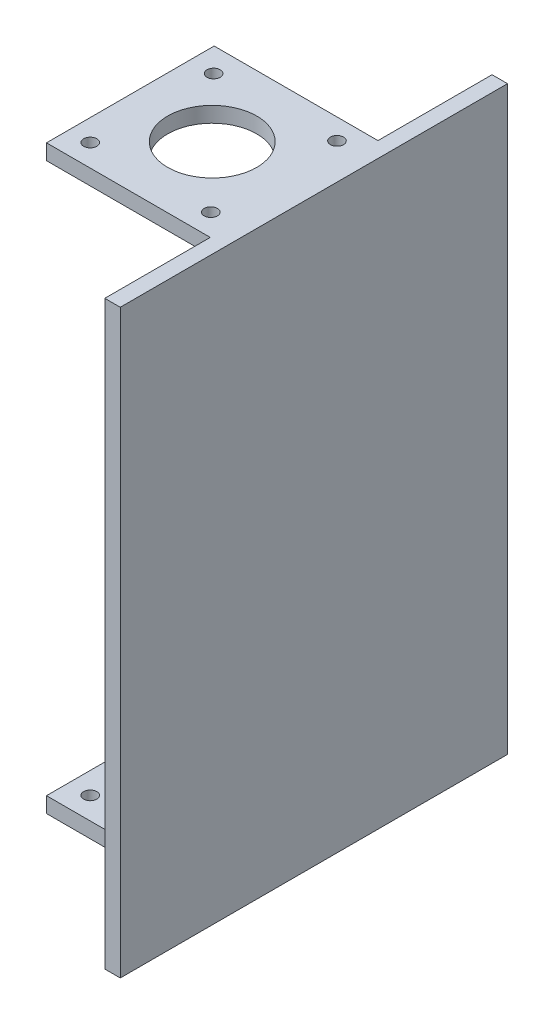
SolidWorks part; units mm, degrees
ref_plane "Front Plane" through (0, 0, 0) normal (0, 0, 1) x (1, 0, 0)
ref_plane "Top Plane" through (0, 0, 0) normal (0, 1, 0) x (1, 0, 0)
ref_plane "Right Plane" through (0, 0, 0) normal (1, 0, 0) x (0, 0, -1)
sketch "Sketch2" plane through (0, 0, 0) normal (0, 1, 0) x (1, 0, 0)
  line L1 (-21.15, -21.65) -> (21.15, -21.65)
  line L2 (-21.15, -21.65) -> (-21.15, 21.65)
  line L3 (-21.15, 21.65) -> (21.15, 21.65)
  line L4 (21.15, -21.65) -> (21.15, 21.65)
  line L5 (-21.15, -21.65) -> (21.15, 21.65) construction
  line L6 (-21.15, 21.65) -> (21.15, -21.65) construction
  circle A0 centre (-15.0694, 15.4256) radius 1.7
  circle A1 centre (15.9184, 16.2948) radius 1.7
  circle A2 centre (15.5664, -15.9344) radius 1.7
  circle A3 centre (-15.5664, -15.9344) radius 1.7
  circle A4 centre (0, 0) radius 11.5
  point P0 (0, 0)
  dimension "D4" = 3.4
  dimension "D5" = 23
  dimension "D1" = 43.3
  dimension "D2" = 42.3
  dimension "D3" = 31
extrude "Boss-Extrude1" add sketch "Sketch2" along normal blind 4
ref_plane "Plane1" through (-21.15, 0, -21.65) normal (-1, 0, 0) x (0, 0, 1)
sketch "Sketch6" plane through (0, 0, -21.65) normal (0, 0, -1) x (-1, 0, 0)
  line L0 (0, 0) -> (28.2537, 0) construction
ref_plane "Plane3" through (-21.15, 4, -21.65) normal (-1, 0, 0) x (0, 0, 1)
ref_plane "Plane4" through (-21.15, 4, -21.65) normal (0, 0, 1) x (1, 0, 0)
ref_plane "Plane5" through (21.15, 4, 21.65) normal (1, 0, 0) x (0, 0, -1)
sketch "Sketch10" plane through (21.15, 4, 21.65) normal (1, 0, 0) x (0, 0, -1)
  line L0 (0, 0) -> (-9.5873, 0) construction
  line L1 (-27.2441, 0) -> (72.7559, 0)
  line L2 (72.7559, 0) -> (72.7559, -150)
  line L3 (-27.2441, 0) -> (-27.2441, -150)
  line L4 (-27.2441, -150) -> (72.7559, -150)
  dimension "D1" = 100
  dimension "D2" = 150
extrude "Boss-Extrude3" add sketch "Sketch10" along normal blind 4
ref_plane "Plane6" through (0, -71, 0) normal (0, -1, 0) x (-1, 0, 0)
mirror "Mirror3" about plane through (0, -71, 0) normal (0, -1, 0) of "Boss-Extrude1"
